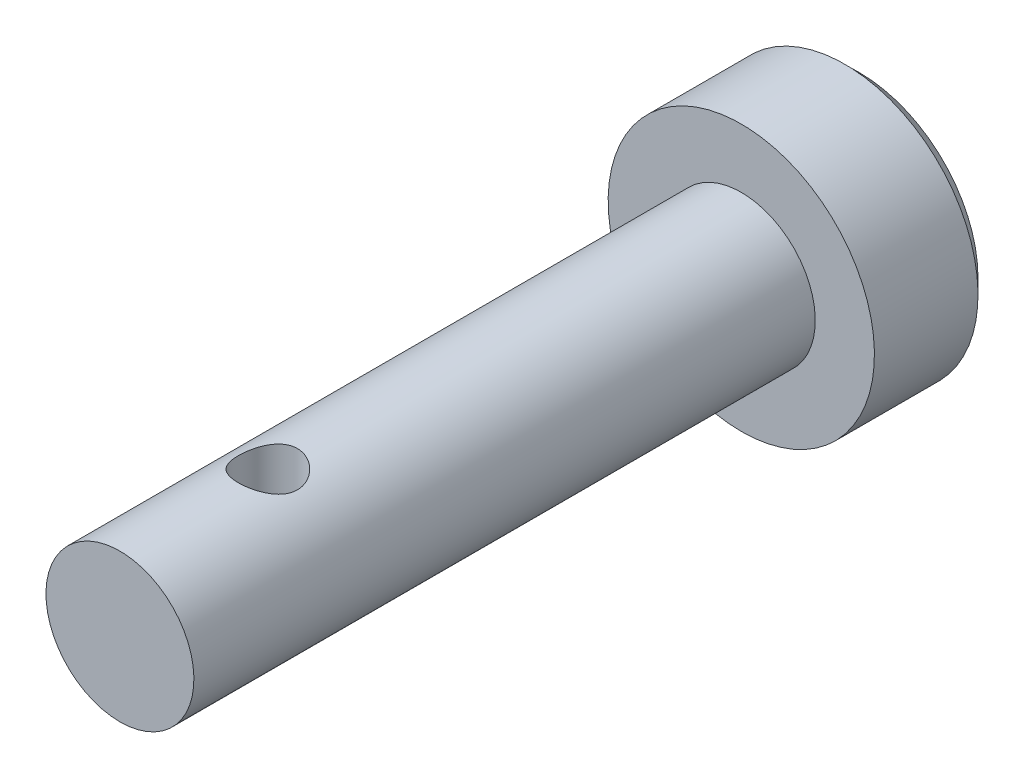
SolidWorks part; units mm, degrees
ref_plane "前视基准面" through (0, 0, 0) normal (0, 0, 1) x (1, 0, 0)
ref_plane "上视基准面" through (0, 0, 0) normal (0, 1, 0) x (1, 0, 0)
ref_plane "右视基准面" through (0, 0, 0) normal (1, 0, 0) x (0, 0, -1)
sketch "草图1" plane through (0, 0, 0) normal (1, 0, 0) x (0, 0, -1)
  line L0 (0, 0) -> (0, 9)
  line L1 (0, 9) -> (-8, 9)
  line L2 (-8, 9) -> (-8, 5)
  line L3 (-8, 5) -> (-50, 5)
  line L4 (-50, 5) -> (-50, 0)
  line L5 (-50, 0) -> (0, 0) construction
  line L6 (0, 0) -> (-50, 0)
  dimension "D1" = 10
  dimension "D2" = 18
  dimension "D3" = 50
  dimension "D4" = 8
revolve "旋转1" add sketch "草图1" angle 360 about L5
ref_plane "基准面1" through (0, 5, 0) normal (0, 1, 0) x (1, 0, 0)
sketch "草图3" plane through (0, 5, 0) normal (0, 1, 0) x (1, 0, 0)
  line L0 (0, -50) -> (0, -40) construction
  line L1 (-5, -50) -> (5, -50) construction
  dimension "D1" = 10
hole_wizard "大小mm 暗销孔1" positions "3D草图1" profile "草图2" hole size "Ø4.0" standard "GB" end condition through all
sketch3d "3D草图1"
  point P0 (0, 5, 40)
sketch "草图2" plane through (0, 5, 40) normal (1, 0, 0) x (0, 0, 1)
  line L0 (0, 0) -> (0, 14)
  line L1 (0, 14) -> (2, 14)
  line L2 (2, 14) -> (2, 0)
  line L5 (2, 0) -> (0, 0)
  line L11 (0, -6.35) -> (0, 107.95) construction
  dimension "通孔孔直径" = 4
  dimension "通孔孔深度" = 14
chamfer "倒角1" distance 1 angle 45 1 edges at (0, -9, 0)
